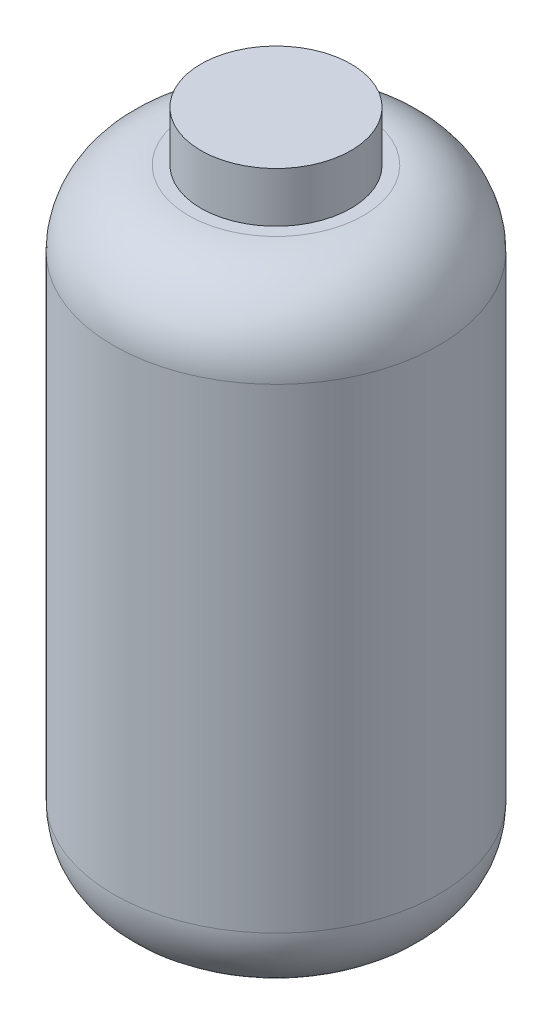
SolidWorks part; units mm, degrees
ref_plane "Front Plane" through (0, 0, 0) normal (0, 0, 1) x (1, 0, 0)
ref_plane "Top Plane" through (0, 0, 0) normal (0, 1, 0) x (1, 0, 0)
ref_plane "Right Plane" through (0, 0, 0) normal (1, 0, 0) x (0, 0, -1)
sketch "Sketch1" plane through (0, 0, 0) normal (0, 1, 0) x (1, 0, 0)
  circle A0 centre (0, 0) radius 32.5
  dimension "D1" = 65
extrude "Boss-Extrude1" add sketch "Sketch1" along normal blind 125
fillet "Fillet1" radius 15 2 edges at (0, 0, 32.5) (0, 125, 32.5)
sketch "Sketch2" plane through (0, 125, 0) normal (0, 1, 0) x (1, 0, 0)
  circle A0 centre (0, 0) radius 15
  dimension "D1" = 30
extrude "Boss-Extrude2" add sketch "Sketch2" along normal blind 10 separate body
